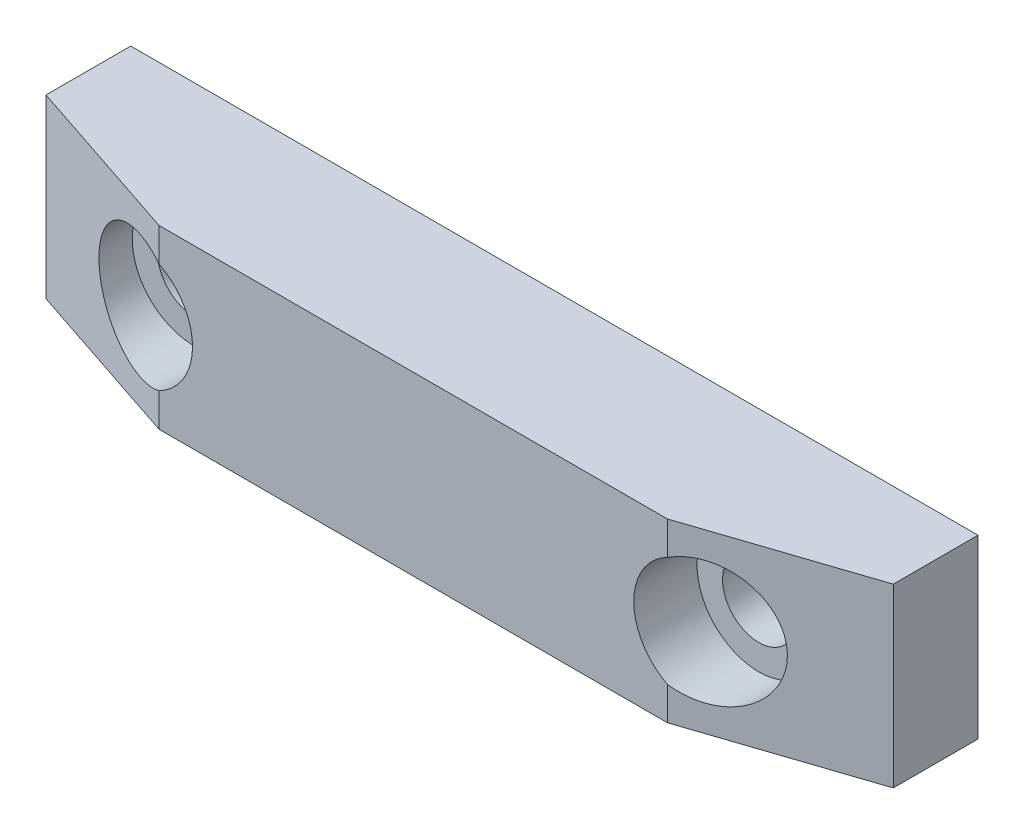
SolidWorks part; units mm, degrees
ref_plane "Front Plane" through (0, 0, 0) normal (0, 0, 1) x (1, 0, 0)
ref_plane "Top Plane" through (0, 0, 0) normal (0, 1, 0) x (1, 0, 0)
ref_plane "Right Plane" through (0, 0, 0) normal (1, 0, 0) x (0, 0, -1)
sketch "Sketch2" plane through (0, 0, 0) normal (0, 1, 0) x (1, 0, 0)
  line L1 (0, 0) -> (38.1, 0)
  line L2 (0, 0) -> (0, 6.35)
  line L3 (0, 6.35) -> (38.1, 6.35)
  line L4 (38.1, 0) -> (38.1, 6.35)
  dimension "D1" = 38.1
  dimension "D2" = 6.35
extrude "Boss-Extrude2" add sketch "Sketch2" along normal blind 7.9375
hole_wizard "CBORE for #4 Socket Head Cap Screw1" positions "3DSketch1" profile "Sketch3" counterbore size "#4" standard "ANSI Inch" end condition through all
sketch3d "3DSketch1"
  line L0 (0, 0, 0) -> (38.1, 0, 0) construction
  line L1 (0, 7.9375, 0) -> (0, 0, 0) construction
  line L2 (38.1, 7.9375, 0) -> (38.1, 0, 0) construction
  point P0 (6.35, 3.9688, 0)
  point P2 (31.75, 3.9688, 0)
  dimension "D1" = 3.9688
  dimension "D2" = 6.35
  dimension "D3" = 6.35
sketch "Sketch3" plane through (6.35, 3.9688, 0) normal (1, 0, 0) x (0, -1, 0)
  line L0 (0, 0) -> (0, 6.35)
  line L1 (0, 6.35) -> (1.6319, 6.35)
  line L3 (1.6319, 6.35) -> (1.632, 2.8448)
  line L4 (1.632, 2.8448) -> (2.7788, 2.8448)
  line L5 (2.7788, 2.8448) -> (2.7788, 0)
  line L7 (2.7788, 0) -> (0, 0)
  line L11 (0, -6.35) -> (0, 107.95) construction
  dimension "Thru Hole Dia." = 3.2639
  dimension "Thru Hole Depth" = 6.35
  dimension "C'Bore Dia." = 5.5575
  dimension "C'Bore Depth" = 2.8448
sketch "Sketch4" plane through (0, 7.9375, 0) normal (0, 1, 0) x (1, 0, 0)
  line L0 (0, 0) -> (0, 2.54)
  line L1 (0, 6.35) -> (0, 0) construction
  line L2 (0, 2.54) -> (7.62, 0)
  line L3 (0, 0) -> (38.1, 0) construction
  line L4 (7.62, 0) -> (0, 0)
  line L5 (38.1, 2.54) -> (30.48, 0)
  line L6 (38.1, 0) -> (38.1, 6.35) construction
  line L7 (30.48, 0) -> (38.1, 0)
  line L8 (38.1, 0) -> (38.1, 2.54)
  dimension "D1" = 7.62
  dimension "D2" = 7.62
  dimension "D3" = 2.54
extrude "Cut-Extrude1" cut sketch "Sketch4" against normal blind 12.7
